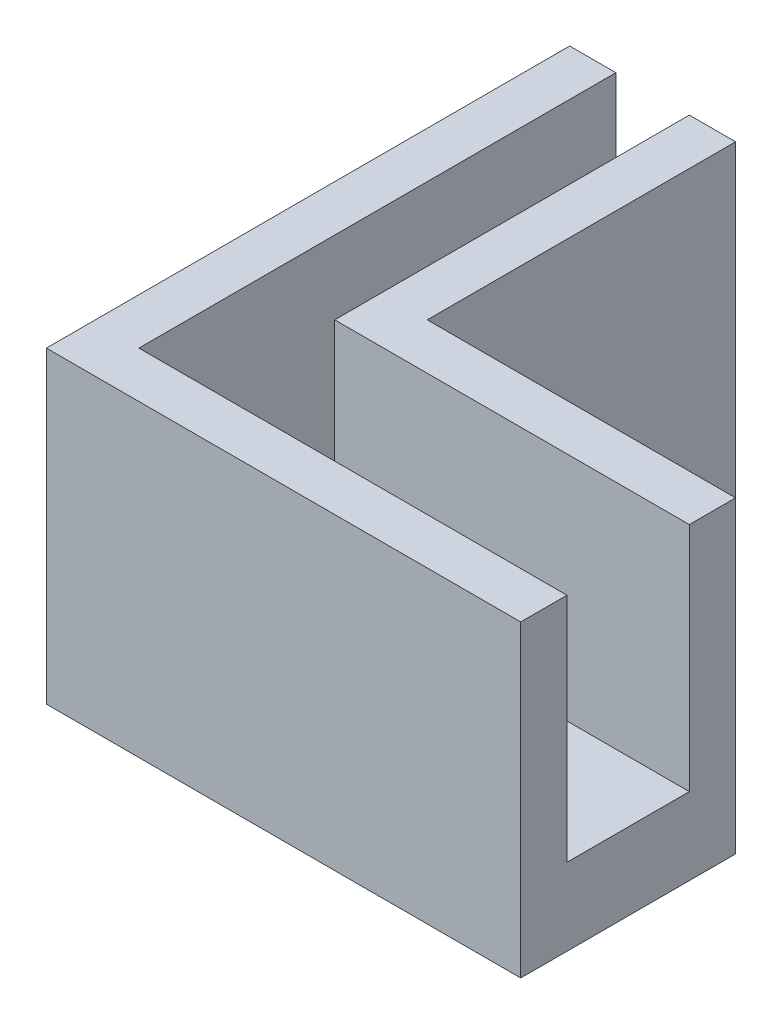
SolidWorks part; units mm, degrees
ref_plane "Front Plane" through (0, 0, 0) normal (0, 0, 1) x (1, 0, 0)
ref_plane "Top Plane" through (0, 0, 0) normal (0, 1, 0) x (1, 0, 0)
ref_plane "Right Plane" through (0, 0, 0) normal (1, 0, 0) x (0, 0, -1)
sketch "Sketch1" plane through (0, 0, 0) normal (0, 1, 0) x (1, 0, 0)
  line L0 (0, 0) -> (4.7625, 0)
  line L4 (4.7625, 0) -> (24.7625, 0)
  line L6 (24.7625, 7.9375) -> (4.7625, 7.9375)
  line L7 (4.7625, 7.9375) -> (4.7625, 27.9375)
  line L9 (0, 27.9375) -> (0, 0)
  line L11 (24.7625, 10.9375) -> (7.7625, 10.9375)
  line L12 (7.7625, 10.9375) -> (7.7625, 27.9375)
  line L14 (-3, 27.9375) -> (-3, -3)
  line L15 (-3, -3) -> (24.7625, -3)
  line L20 (-3, 27.9375) -> (-3, 30.9375)
  line L21 (-3, 30.9375) -> (7.7625, 30.9375)
  line L22 (7.7625, 30.9375) -> (7.7625, 27.9375)
  line L23 (0, 27.9375) -> (4.7625, 27.9375)
  line L24 (24.7625, 7.9375) -> (24.7625, 0)
  line L25 (24.7625, -3) -> (27.7625, -3)
  line L26 (27.7625, -3) -> (27.7625, 10.9375)
  line L27 (27.7625, 10.9375) -> (24.7625, 10.9375)
  dimension "D1" = 4.7625
  dimension "D2" = 20
  dimension "D3" = 7.9375
  dimension "D4" = 20
  dimension "D5" = 3
  dimension "D6" = 3
  dimension "D7" = 3
  dimension "D8" = 3
  dimension "D9" = 3
  dimension "D10" = 3
extrude "Boss-Extrude7" add sketch "Sketch1" along normal blind 15
sketch "Sketch2" plane through (0, 0, 0) normal (0, -1, 0) x (1, 0, 0)
  line L0 (27.7625, 3) -> (27.7625, -10.9375)
  line L1 (27.7625, -10.9375) -> (7.7625, -10.9375)
  line L2 (7.7625, -10.9375) -> (7.7625, -30.9375)
  line L3 (7.7625, -30.9375) -> (-3, -30.9375)
  line L4 (-3, -30.9375) -> (-3, 3)
  line L5 (-3, 3) -> (27.7625, 3)
extrude "Boss-Extrude8" add sketch "Sketch2" along normal blind 5
sketch "Sketch3" plane through (0, 15, 0) normal (0, 1, 0) x (1, 0, 0)
  line L0 (0, 27.9375) -> (4.7625, 27.9375)
  line L2 (4.7625, 27.9375) -> (4.7625, 30.9375)
  line L3 (7.7625, 30.9375) -> (-3, 30.9375) construction
  line L4 (4.7625, 30.9375) -> (0, 30.9375)
  line L5 (0, 30.9375) -> (0, 27.9375)
  line L6 (24.7625, 0) -> (24.7625, 7.9375)
  line L7 (24.7625, 7.9375) -> (27.7625, 7.9375)
  line L8 (27.7625, -3) -> (27.7625, 10.9375) construction
  line L9 (27.7625, 7.9375) -> (27.7625, 0)
  line L10 (27.7625, 0) -> (24.7625, 0)
extrude "Cut-Extrude1" cut sketch "Sketch3" against normal up to surface (15 mm away) up to face at (9.8417, 0, -11.9583)
